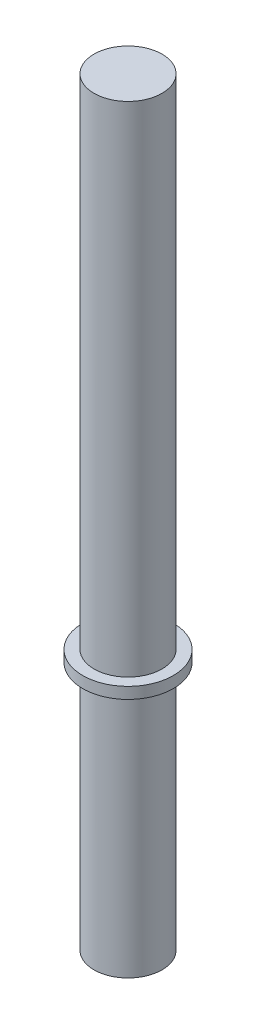
SolidWorks part; units mm, degrees
ref_plane "前视基准面" through (0, 0, 0) normal (0, 0, 1) x (1, 0, 0)
ref_plane "上视基准面" through (0, 0, 0) normal (0, 1, 0) x (1, 0, 0)
ref_plane "右视基准面" through (0, 0, 0) normal (1, 0, 0) x (0, 0, -1)
sketch "草图1" plane through (0, 0, 0) normal (0, 1, 0) x (1, 0, 0)
  circle A0 centre (0, 0) radius 1.5
extrude "凸台-拉伸1" add sketch "草图1" along normal blind 33.5
sketch "草图2" plane through (0, 0, 0) normal (0, -1, 0) x (1, 0, 0)
  circle A0 centre (0, 0) radius 1.5
  circle A1 centre (0, 0) radius 2
extrude "凸台-拉伸2" add sketch "草图2" against normal blind 0.5 from offset 11
